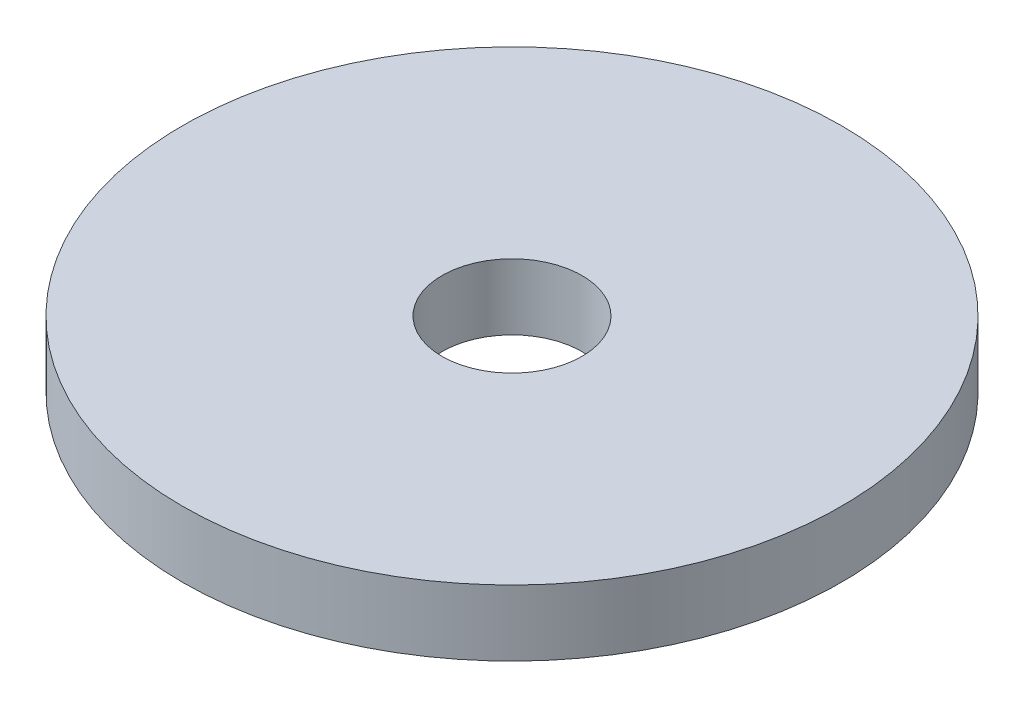
SolidWorks part; units mm, degrees
material "Thornel Mat VMA"
ref_plane "前视基准面" through (0, 0, 0) normal (0, 0, 1) x (1, 0, 0)
ref_plane "上视基准面" through (0, 0, 0) normal (0, 1, 0) x (1, 0, 0)
ref_plane "右视基准面" through (0, 0, 0) normal (1, 0, 0) x (0, 0, -1)
sketch "草图1" plane through (0, 0, 0) normal (0, 1, 0) x (1, 0, 0)
  circle A0 centre (0, 0) radius 10
  circle A1 centre (0, 0) radius 2.125
  dimension "D1" = 20
  dimension "D2" = 4.25
extrude "凸台-拉伸1" add sketch "草图1" along normal blind 2
